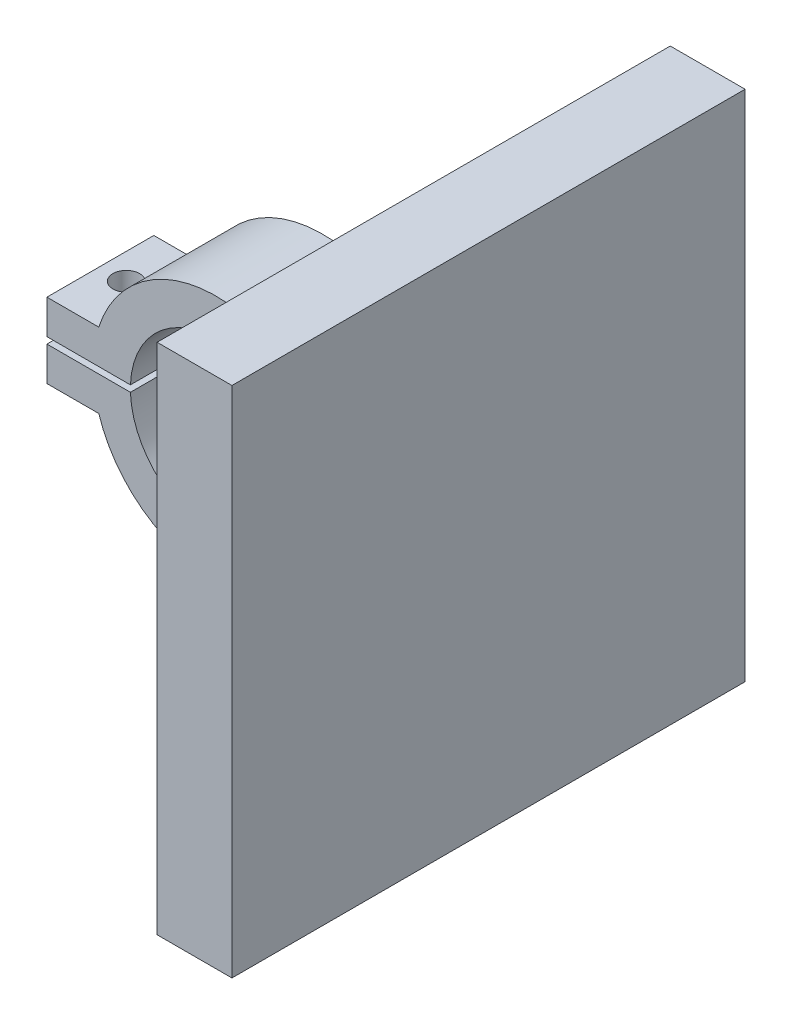
SolidWorks part; units mm, degrees
ref_plane "Alzado" through (0, 0, 0) normal (0, 0, 1) x (1, 0, 0)
ref_plane "Planta" through (0, 0, 0) normal (0, 1, 0) x (1, 0, 0)
ref_plane "Vista lateral" through (0, 0, 0) normal (1, 0, 0) x (0, 0, -1)
sketch "Croquis1" plane through (0, 0, 0) normal (0, 0, 1) x (1, 0, 0)
  line L0 (0, 0) -> (-15.4227, 0) construction
  line L1 (0, 0) -> (19.65, 0) construction
  line L2 (-7.9031, 1.75) -> (-3.5969, 1.75)
  line L3 (-7.9031, 1.75) -> (-7.9031, -1.75)
  line L4 (-7.9031, -1.75) -> (-3.5969, -1.75)
  line L5 (-3.5969, 1.75) -> (-3.5969, -1.75)
  line L6 (-7.9031, 1.75) -> (-3.5969, -1.75) construction
  line L7 (-7.9031, -1.75) -> (-3.5969, 1.75) construction
  line L8 (-8.2857, 0.15) -> (-1.3962, 0.15)
  line L9 (-8.2857, 0.15) -> (-8.2857, -0.15)
  line L10 (-8.2857, -0.15) -> (-1.3962, -0.15)
  line L11 (-1.3962, 0.15) -> (-1.3962, -0.15)
  line L12 (-8.2857, 0.15) -> (-1.3962, -0.15) construction
  line L13 (-8.2857, -0.15) -> (-1.3962, 0.15) construction
  line L15 (4.7493, 2) -> (6.7507, 2)
  line L16 (4.7493, 2) -> (4.7493, -2)
  line L17 (4.7493, -2) -> (6.7507, -2)
  line L18 (6.7507, 2) -> (6.7507, -2)
  line L19 (4.7493, 2) -> (6.7507, -2) construction
  line L20 (4.7493, -2) -> (6.7507, 2) construction
  circle A0 centre (0, 0) radius 5.75
  circle A1 centre (0, 0) radius 4
  point P4 (-5.75, 0)
  point P6 (-4.8409, 0)
  point P7 (-5.75, 0)
  point P12 (-4.8409, 0)
  point P17 (5.75, 0)
  point P19 (5.75, 0)
  dimension "D1" = 8
  dimension "D2" = 11.5
  dimension "D3" = 3.5
  dimension "D4" = 0.3
  dimension "D5" = 4
extrude "Saliente-Extruir3" add sketch "Croquis1" along normal blind 5 contours A1 L4 A0 L17 L16 L15 L2 | A0 L10 L3 L4 | A0 L2 L3 L8 | A1 L2 A0 L8 | A1 L10 A0 L4 | A0 L17 L18 L15 | L17 A0 L15 L16
sketch "Croquis5" plane through (0, 0, 0) normal (0, 1, 0) x (1, 0, 0)
  line L0 (0, 0) -> (-9.268, 0) construction
  line L1 (-9.268, 0) -> (-7.9031, 0) construction
  line L2 (-7.9031, 0) -> (-7.9031, -2.5) construction
  line L3 (-7.9031, -5) -> (-7.9031, 0) construction
  line L4 (-7.9031, -2.5) -> (-5.4772, -2.5) construction
  line L5 (-5.4772, -5) -> (-5.4772, 0) construction
  circle A0 centre (-6.6902, -2.5) radius 0.625
  dimension "D1" = 1.25
extrude "Cortar-Extruir2" cut sketch "Croquis5" against normal through all both and the other way through all
sketch "Croquis7" plane through (6.7507, 0, 0) normal (1, 0, 0) x (0, 0, -1)
  line L0 (-8.3369, 0) -> (4.5523, 0) construction
  line L6 (-14.5, 12) -> (9.5, 12)
  line L7 (-14.5, 12) -> (-14.5, -12)
  line L8 (-14.5, -12) -> (9.5, -12)
  line L9 (9.5, 12) -> (9.5, -12)
  line L10 (-14.5, 12) -> (9.5, -12) construction
  line L11 (-14.5, -12) -> (9.5, 12) construction
  point P3 (-2.5, 0)
  point P4 (-2.5, 0)
  point P5 (-2.5, 0)
  dimension "D1" = 2.5
  dimension "D2" = 24
  dimension "D3" = 24
extrude "Saliente-Extruir5" add sketch "Croquis7" along normal blind 3.5
